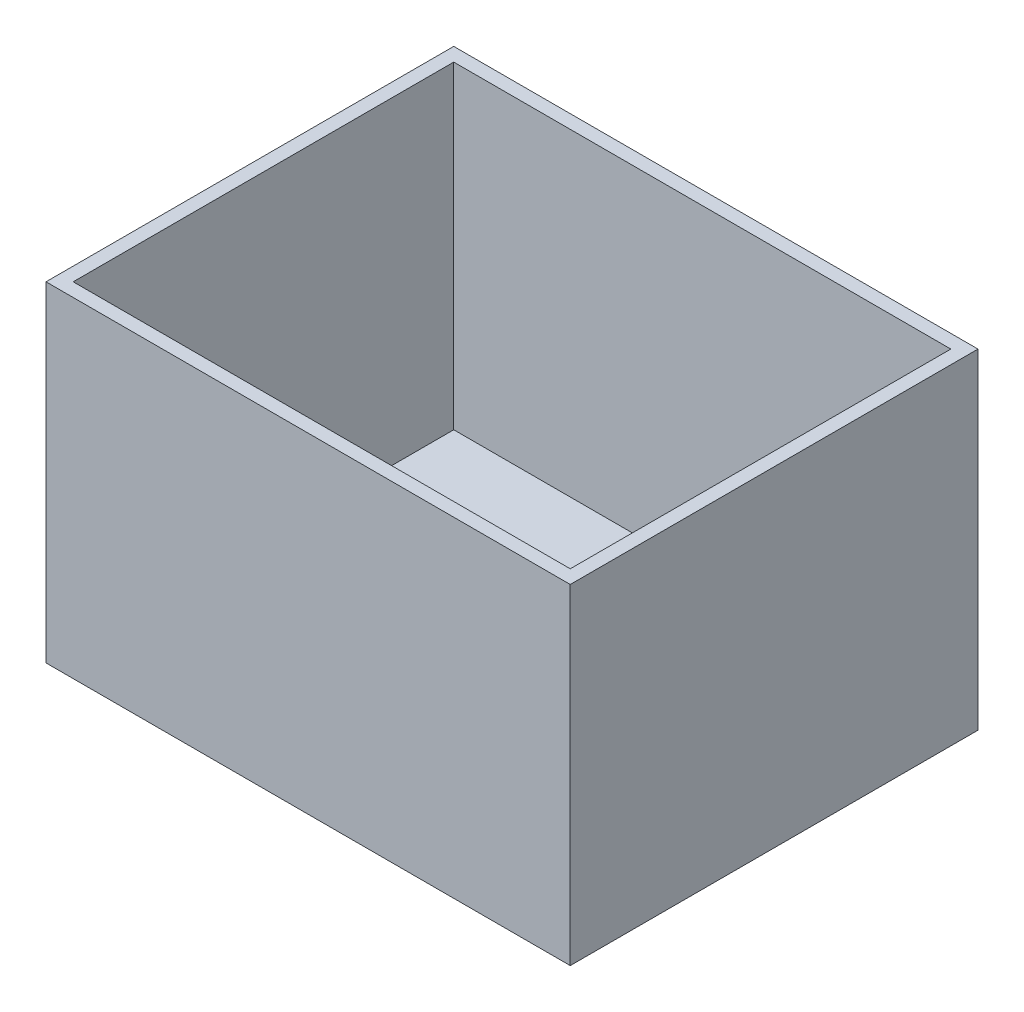
SolidWorks part; units mm, degrees
ref_plane "Front Plane" through (0, 0, 0) normal (0, 0, 1) x (1, 0, 0)
ref_plane "Top Plane" through (0, 0, 0) normal (0, 1, 0) x (1, 0, 0)
ref_plane "Right Plane" through (0, 0, 0) normal (1, 0, 0) x (0, 0, -1)
sketch "Sketch1" plane through (0, 0, 0) normal (0, 1, 0) x (1, 0, 0)
  line L1 (-135, -105) -> (135, -105)
  line L2 (-135, -105) -> (-135, 105)
  line L3 (-135, 105) -> (135, 105)
  line L4 (135, -105) -> (135, 105)
  line L5 (-128, -98) -> (128, -98)
  line L6 (-128, -98) -> (-128, 98)
  line L7 (-128, 98) -> (128, 98)
  line L8 (128, -98) -> (128, 98)
extrude "Cover_Walls" add sketch "Sketch1" along normal blind 170
sketch "Sketch2" plane through (0, 0, 0) normal (0, 1, 0) x (1, 0, 0)
  line L1 (-135, -105) -> (135, -105)
  line L2 (-135, -105) -> (-135, 105)
  line L3 (-135, 105) -> (135, 105)
  line L4 (135, -105) -> (135, 105)
extrude "Cover_Roof" add sketch "Sketch2" along normal blind 6
equation "\"ValveDiameter\" = 50mm"
equation "\"MotorGearTeeth\" = 40"
equation "\"OutputGearTeeth\" = 80"
equation "\"GearModule\" = 1.5mm"
equation "\"PressureAngle\" = 20deg"
equation "\"GearCenterDistance\" = 90mm"
equation "\"GearWidth\" = 18mm"
equation "\"OutputShaftDiameter\" = 20mm"
equation "\"BearingOD\" = 47mm"
equation "\"BearingWidth\" = 14mm"
equation "\"PlateThickness\" = 6mm"
equation "\"ValveRotation\" = 90deg"
